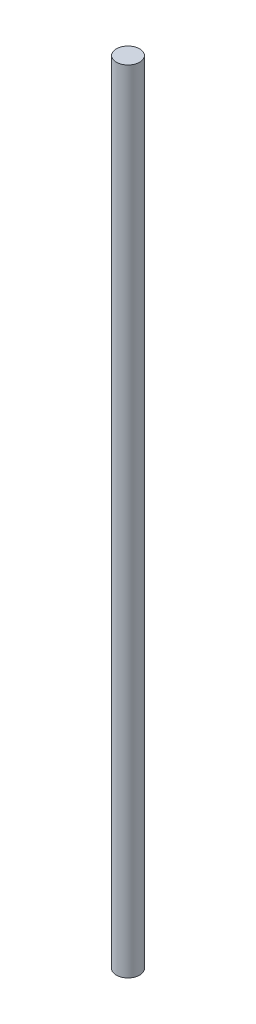
SolidWorks part; units mm, degrees
ref_plane "前视基准面" through (0, 0, 0) normal (0, 0, 1) x (1, 0, 0)
ref_plane "上视基准面" through (0, 0, 0) normal (0, 1, 0) x (1, 0, 0)
ref_plane "右视基准面" through (0, 0, 0) normal (1, 0, 0) x (0, 0, -1)
sketch "草图1" plane through (0, 0, 0) normal (0, 1, 0) x (1, 0, 0)
  circle A0 centre (-10.3411, 6.948) radius 2.5
extrude "凸台-拉伸1" add sketch "草图1" along normal blind 170
